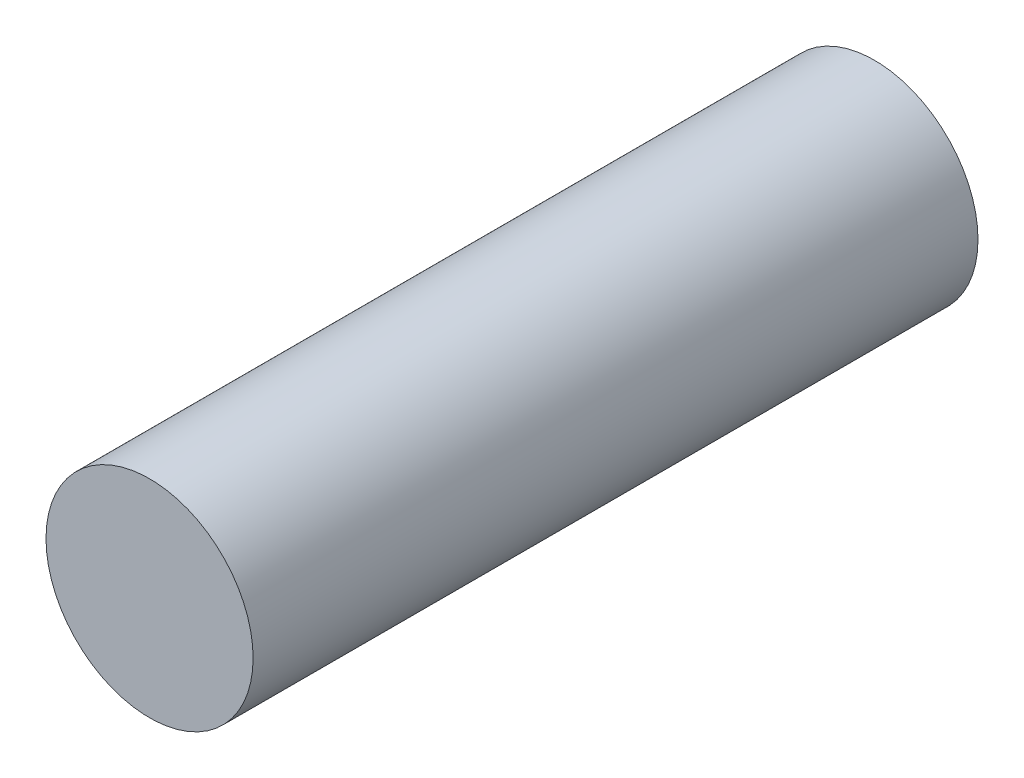
SolidWorks part; units mm, degrees
ref_plane "Front Plane" through (0, 0, 0) normal (0, 0, 1) x (1, 0, 0)
ref_plane "Top Plane" through (0, 0, 0) normal (0, 1, 0) x (1, 0, 0)
ref_plane "Right Plane" through (0, 0, 0) normal (1, 0, 0) x (0, 0, -1)
sketch "Sketch1" plane through (0, 0, 0) normal (0, 0, 1) x (1, 0, 0)
  circle A0 centre (0, 0) radius 10
extrude "Boss-Extrude1" add sketch "Sketch1" along normal blind 70
